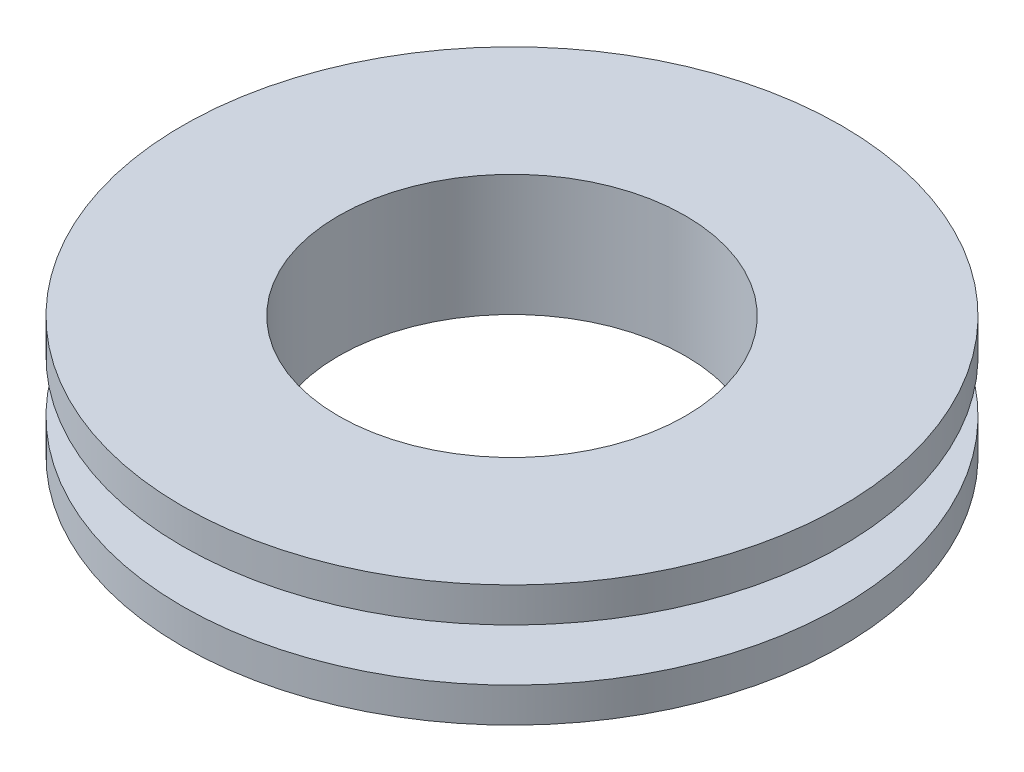
SolidWorks part; units mm, degrees
material "橡胶"
ref_plane "前视基准面" through (0, 0, 0) normal (0, 0, 1) x (1, 0, 0)
ref_plane "上视基准面" through (0, 0, 0) normal (0, 1, 0) x (1, 0, 0)
ref_plane "右视基准面" through (0, 0, 0) normal (1, 0, 0) x (0, 0, -1)
other "Configuration Table"
sketch "草图1" plane through (0, 0, 0) normal (0, 1, 0) x (1, 0, 0)
  circle A0 centre (0, 0) radius 5
  circle A1 centre (0, 0) radius 9.5
  dimension "D1" = 10
  dimension "D2" = 19
extrude "凸台-拉伸1" add sketch "草图1" along normal blind 1
sketch "草图2" plane through (0, 1, 0) normal (0, 1, 0) x (1, 0, 0)
  circle A0 centre (0, 0) radius 5
  circle A1 centre (0, 0) radius 6
  dimension "D1" = 12
extrude "凸台-拉伸2" add sketch "草图2" along normal blind 1.5 contours A1 | A0
sketch "草图3" plane through (0, 2.5, 0) normal (0, 1, 0) x (1, 0, 0)
  circle A0 centre (0, 0) radius 9.5
  circle A1 centre (0, 0) radius 5
extrude "凸台-拉伸3" add sketch "草图3" along normal blind 1 contours A0 | A1
